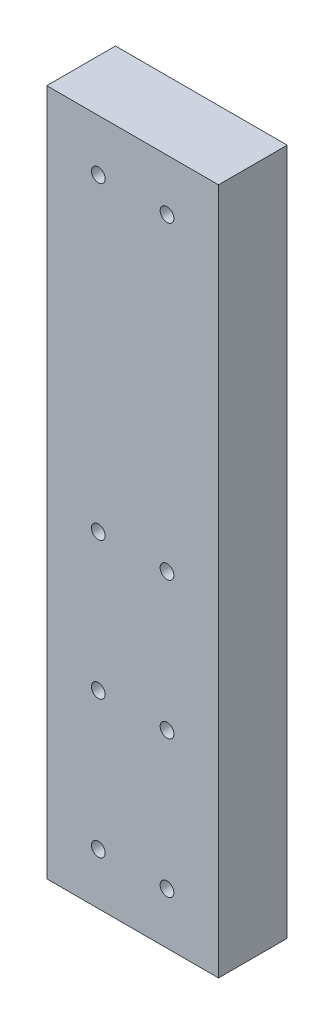
SolidWorks part; units mm, degrees
material "Balsa"
ref_plane "Plan de face" through (0, 0, 0) normal (0, 0, 1) x (1, 0, 0)
ref_plane "Plan de dessus" through (0, 0, 0) normal (0, 1, 0) x (1, 0, 0)
ref_plane "Plan de droite" through (0, 0, 0) normal (1, 0, 0) x (0, 0, -1)
sketch "Sketch1" plane through (0, 0, 0) normal (0, 0, 1) x (1, 0, 0)
  line L1 (0, 0) -> (25, 0)
  line L2 (0, 0) -> (0, 100)
  line L3 (0, 100) -> (25, 100)
  line L4 (25, 0) -> (25, 100)
  dimension "D1" = 25
  dimension "D2" = 100
extrude "Boss-Extrude1" add sketch "Sketch1" along normal blind 10
sketch "Sketch2" plane through (0, 0, 10) normal (0, 0, 1) x (1, 0, 0)
  line L0 (12.5, 100) -> (12.5, 0) construction
  line L1 (25, 100) -> (0, 100) construction
  line L2 (0, 0) -> (25, 0) construction
  line L3 (7.5, 92.5) -> (7.5, 0) construction
  line L4 (0, 92.5) -> (25, 92.5) construction
  line L5 (0, 100) -> (0, 0) construction
  line L6 (25, 0) -> (25, 100) construction
  circle A0 centre (7.5, 92.5) radius 1
  circle A1 centre (7.5, 47.5) radius 1
  circle A2 centre (7.5, 27.5) radius 1
  circle A3 centre (7.5, 7.5) radius 1
  circle A4 centre (17.5, 92.5) radius 1
  circle A5 centre (17.5, 7.5) radius 1
  circle A6 centre (17.5, 27.5) radius 1
  circle A7 centre (17.5, 47.5) radius 1
  dimension "D1" = 2
  dimension "D2" = 2
  dimension "D3" = 2
  dimension "D4" = 20
  dimension "D5" = 45
  dimension "D6" = 5
  dimension "D8" = 2
  dimension "D7" = 7.5
  dimension "D9" = 20
extrude "Cut-Extrude1" cut sketch "Sketch2" against normal through all contours A0 | A7 | A1 | A6 | A2 | A5 | A3 | A4
